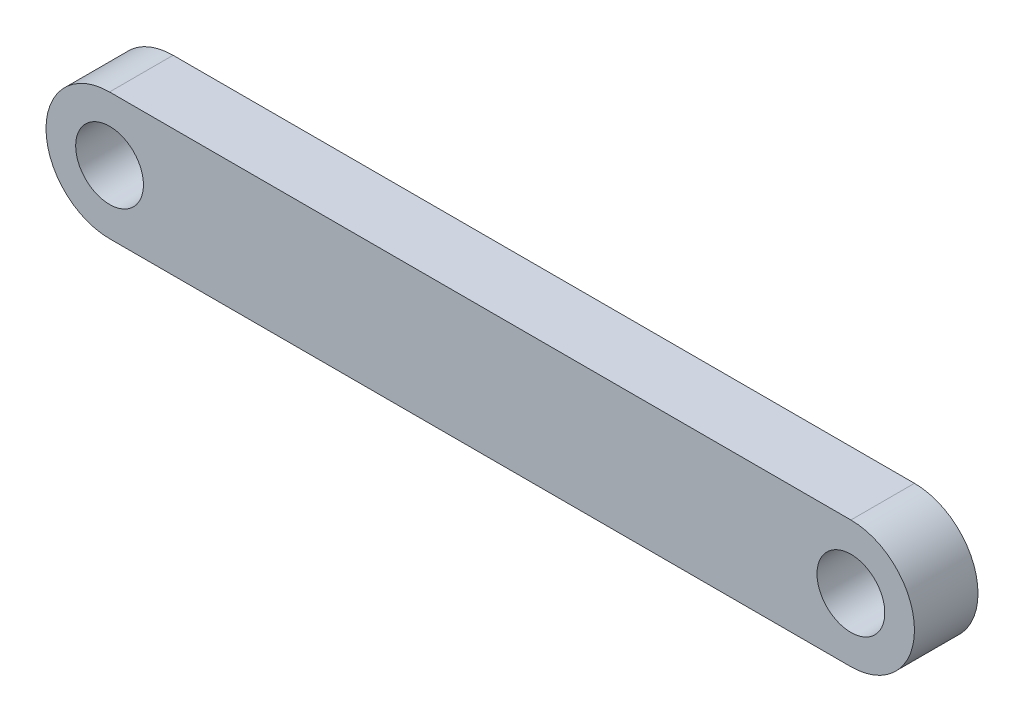
SolidWorks part; units mm, degrees
ref_plane "Plan de face" through (0, 0, 0) normal (0, 0, 1) x (1, 0, 0)
ref_plane "Plan de dessus" through (0, 0, 0) normal (0, 1, 0) x (1, 0, 0)
ref_plane "Plan de droite" through (0, 0, 0) normal (1, 0, 0) x (0, 0, -1)
ref_plane "Plan1" through (0, 0, 3) normal (0, 0, 1) x (1, 0, 0)
sketch "Esquisse1" plane through (0, 0, 3) normal (0, 0, 1) x (1, 0, 0)
  line L0 (35, 3) -> (0, 3)
  line L1 (0, -3) -> (35, -3)
  arc A0 (0, 3) -> (0, -3) centre (0, 0) ccw
  arc A1 (35, -3) -> (35, 3) centre (35, 0) ccw
  circle A2 centre (35, 0) radius 1.6
  circle A3 centre (0, 0) radius 1.6
extrude "Boss.-Extru.1" add sketch "Esquisse1" against normal blind 3
